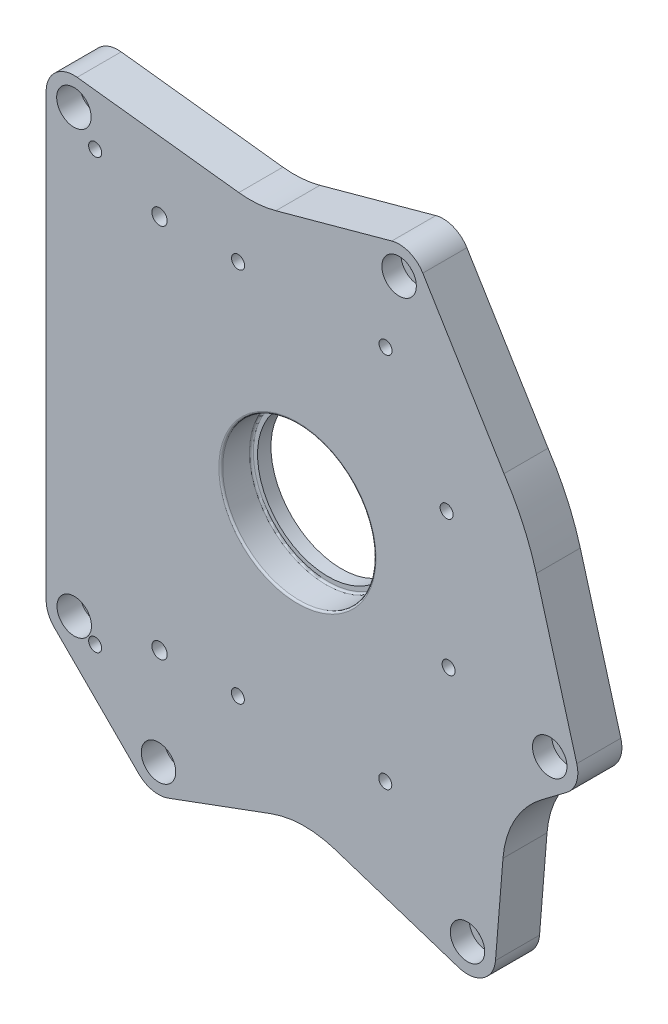
SolidWorks part; units mm, degrees
material "6061-T6 (SS)"
ref_plane "Front Plane" through (0, 0, 0) normal (0, 0, 1) x (1, 0, 0)
ref_plane "Top Plane" through (0, 0, 0) normal (0, 1, 0) x (1, 0, 0)
ref_plane "Right Plane" through (0, 0, 0) normal (1, 0, 0) x (0, 0, -1)
sketch "Sketch1" plane through (0, 0, 0) normal (0, 0, 1) x (1, 0, 0)
  line L0 (84.2211, -163.4901) -> (2.6993, -136.8316)
  line L1 (-67.4584, -162.7302) -> (2.6993, -136.8316)
  line L2 (-82.9108, -159.3414) -> (-126.9141, -115.3364)
  line L3 (140.5448, -56.1387) -> (109.1493, -79.774)
  line L4 (103.4012, -150.7323) -> (109.1493, -79.774)
  line L5 (145.8454, -40.4558) -> (124.6838, 34.9416)
  line L6 (65.4504, 141.1198) -> (107.841, 71.6428)
  line L9 (49.2431, 147.5528) -> (-20.7968, 128.3749)
  line L13 (-115.0226, 139.4368) -> (-20.7968, 128.3749)
  line L14 (-131.2133, 125.0355) -> (-131.2102, -104.9645)
  arc A2 (-115.0226, 139.4368) -> (-131.2133, 125.0355) centre (-116.7133, 125.0357) ccw
  circle A3 centre (-116.7133, 125.0357) radius 3.5 construction
  arc A6 (65.4504, 141.1198) -> (49.2431, 147.5528) centre (53.0725, 133.5676) ccw
  circle A7 centre (-76.5534, 103.7539) radius 2.5 construction
  arc A9 (-131.2102, -104.9645) -> (-126.9141, -115.3364) centre (-116.5415, -104.9643) ccw
  circle A10 centre (-116.5415, -104.9643) radius 3.5 construction
  arc A12 (-82.9108, -159.3414) -> (-67.4584, -162.7302) centre (-72.5383, -148.9692) ccw
  circle A13 centre (-72.5383, -148.9692) radius 3.5 construction
  arc A15 (84.2211, -163.4901) -> (103.4012, -150.7323) centre (88.7803, -149.548) ccw
  arc A17 (140.5448, -56.1387) -> (145.8454, -40.4558) centre (131.7224, -44.4197) ccw
  circle A18 centre (59.1026, -114.9804) radius 2.5 construction
  circle A23 centre (88.7803, -149.548) radius 3.5 construction
  circle A27 centre (131.7224, -44.4197) radius 3.5 construction
  arc A30 (124.6838, 34.9416) -> (107.841, 71.6428) centre (-0.017, -0.0702) ccw
  circle A31 centre (53.0725, 133.5676) radius 3.5 construction
  dimension "D1" = 14.5
  dimension "D2" = 7
  dimension "D3" = 5
extrude "Boss-Extrude1" add sketch "Sketch1" along normal blind 23 contours L5 A30 L6 A6 L9 L13 A2 L14 A9 L2 A12 L1 L0 A15 L4 L3 A17 A31 A3 A7 A10 A13 A18 A23 A27
fillet "Fillet2" radius 50.8 3 edges at (-20.7968, 128.3749, 11.5) (109.1493, -79.774, 11.5) (2.6993, -136.8316, 11.5)
sketch "Sketch2" plane through (0, 0, 23) normal (0, 0, -1) x (-1, 0, 0)
  circle A0 centre (0, 0) radius 40.05
  dimension "D1" = 80.1
extrude "Cut-Extrude1" cut sketch "Sketch2" along normal blind 16
sketch "Sketch5" plane through (0, 0, 23) normal (0, 0, -1) x (-1, 0, 0)
  circle A0 centre (0, 0) radius 36.83
  dimension "D1" = 73.66
extrude "Cut-Extrude2" cut sketch "Sketch5" along normal blind 25.4
sketch "Sketch6" plane through (0, 0, 0) normal (0, 0, 1) x (1, 0, 0)
  circle A0 centre (0, 0) radius 50.8 construction
  point P14 (0, 0)
  dimension "D2" = 101.6
fillet "Fillet5" radius 1 1 edges at (-40.05, 0, 23)
fillet "Fillet6" radius 1 1 edges at (-40.05, 0, 7)
sketch "Sketch43" plane through (0, 0, 23) normal (0, 0, 1) x (1, 0, 0)
  line L13 (0, 0) -> (150.4649, 0) construction
  line L14 (-31.12, -98.35) -> (-105.6166, -112.2929) construction
  line L15 (-31, 98) -> (-105.6166, 111.6261) construction
  line L16 (-105.6166, -112.2929) -> (-105.6166, 111.6261) construction
  line L17 (0, 0) -> (-105.6166, 111.6261) construction
  line L18 (-31, 98) -> (0, 0) construction
  line L19 (0, 0) -> (46, 97.92) construction
  line L20 (77.9, 39.75) -> (0, 0) construction
  line L21 (0, 0) -> (-72, -98.1221) construction
  line L22 (0, 0) -> (78.925, -30.46) construction
  line L23 (45.85, -98.52) -> (0, 0) construction
  line L24 (0, 0) -> (-72, 97.9779) construction
  line L25 (0, 0) -> (-31.12, -98.35) construction
  line L26 (-105.6166, -112.2929) -> (0, 0) construction
  circle A8 centre (0, 0) radius 46.4211 construction
  circle A12 centre (-46.643, -71.23) radius 11.3319 construction
  circle A13 centre (-72, 97.9779) radius 3.9701
  circle A14 centre (-72, -98.1221) radius 3.9701
  circle A15 centre (-105.6166, 111.6261) radius 3
  circle A16 centre (-31, 98) radius 3
  circle A17 centre (46, 97.92) radius 3
  circle A18 centre (77.9, 39.75) radius 3
  circle A19 centre (78.925, -30.46) radius 3
  circle A20 centre (45.85, -98.52) radius 3
  circle A21 centre (-31.12, -98.35) radius 3
  circle A22 centre (-105.6166, -112.2929) radius 3
  circle A23 centre (0, 0) radius 36.83 construction
  point P2 (44.5749, -98.52)
  dimension "D2" = 45.85
  dimension "D3" = 31.12
  dimension "D1" = 98.52
  dimension "D4" = 98.35
  dimension "D5" = 98.1221
  dimension "D6" = 72
  dimension "D7" = 105.6166
  dimension "D8" = 105.6166
  dimension "D9" = 72
  dimension "D10" = 31
  dimension "D11" = 46
  dimension "D12" = 77.9
  dimension "D13" = 78.925
  dimension "D14" = 39.75
  dimension "D15" = 30.46
  dimension "D16" = 97.92
  dimension "D17" = 98
  dimension "D18" = 97.9779
  dimension "D19" = 111.6261
  dimension "D20" = 112.2929
  dimension "D21" = 196.1
  dimension "D22" = 7.9403
  dimension "D23" = 6
sketch "Sketch59" plane through (0, 0, 23) normal (0, 0, 1) x (1, 0, 0)
  line L0 (145.8454, -40.4558) -> (124.6838, 34.9416) construction
  line L1 (140.5448, -56.1387) -> (127.387, -66.0442) construction
  line L2 (103.4012, -150.7323) -> (107.3061, -102.5275) construction
  line L3 (84.2211, -163.4901) -> (19.4993, -142.3254) construction
  line L4 (-67.4584, -162.7302) -> (-13.8824, -142.9527) construction
  line L5 (-82.9108, -159.3414) -> (-126.9141, -115.3364) construction
  line L6 (65.4504, 141.1198) -> (107.841, 71.6428) construction
  line L7 (49.2431, 147.5528) -> (-11.269, 130.9837) construction
  line L8 (-115.0226, 139.4368) -> (-30.608, 129.5267) construction
  line L9 (-131.2133, 125.0355) -> (-131.2102, -104.9645) construction
  line L10 (145.8454, -40.4558) -> (124.6838, 34.9416)
  line L11 (140.5448, -56.1387) -> (127.387, -66.0442)
  line L12 (103.4012, -150.7323) -> (107.3061, -102.5275)
  line L13 (84.2211, -163.4901) -> (19.4993, -142.3254)
  line L14 (-67.4584, -162.7302) -> (-13.8824, -142.9527)
  line L15 (-82.9108, -159.3414) -> (-126.9141, -115.3364)
  line L16 (65.4504, 141.1198) -> (107.841, 71.6428)
  line L17 (49.2431, 147.5528) -> (-11.269, 130.9837)
  line L18 (-115.0226, 139.4368) -> (-30.608, 129.5267)
  line L19 (-131.2133, 125.0355) -> (-131.2102, -104.9645)
  line L30 (49.2431, 147.5528) -> (-20.7968, 128.3749)
  line L31 (107.841, 71.6428) -> (65.4504, 141.1198)
  line L32 (145.8454, -40.4558) -> (124.6838, 34.9416)
  line L33 (109.1493, -79.774) -> (140.5448, -56.1387)
  line L34 (103.4012, -150.7323) -> (109.1493, -79.774)
  line L35 (2.6993, -136.8316) -> (84.2211, -163.4901)
  line L36 (-67.4584, -162.7302) -> (2.6993, -136.8316)
  line L37 (-126.9141, -115.3364) -> (-82.9108, -159.3414)
  line L38 (-131.2133, 125.0355) -> (-131.2102, -104.9645)
  line L39 (-20.7968, 128.3749) -> (-115.0226, 139.4368)
  line L40 (49.2431, 147.5528) -> (-20.7968, 128.3749)
  line L41 (107.841, 71.6428) -> (65.4504, 141.1198)
  line L42 (145.8454, -40.4558) -> (124.6838, 34.9416)
  line L43 (109.1493, -79.774) -> (140.5448, -56.1387)
  line L44 (103.4012, -150.7323) -> (109.1493, -79.774)
  line L45 (2.6993, -136.8316) -> (84.2211, -163.4901)
  line L46 (-67.4584, -162.7302) -> (2.6993, -136.8316)
  line L47 (-126.9141, -115.3364) -> (-82.9108, -159.3414)
  line L48 (-131.2133, 125.0355) -> (-131.2102, -104.9645)
  line L49 (-20.7968, 128.3749) -> (-115.0226, 139.4368)
  arc A0 (124.6838, 34.9416) -> (107.841, 71.6428) centre (-0.017, -0.0702) ccw construction
  arc A1 (140.5448, -56.1387) -> (145.8454, -40.4558) centre (131.7224, -44.4197) ccw construction
  arc A2 (127.387, -66.0442) -> (107.3061, -102.5275) centre (157.9402, -106.6292) ccw construction
  arc A3 (84.2211, -163.4901) -> (103.4012, -150.7323) centre (88.7803, -149.548) ccw construction
  arc A4 (19.4993, -142.3254) -> (-13.8824, -142.9527) centre (3.7099, -190.6093) ccw construction
  arc A5 (-82.9108, -159.3414) -> (-67.4584, -162.7302) centre (-72.5383, -148.9692) ccw construction
  arc A6 (-131.2102, -104.9645) -> (-126.9141, -115.3364) centre (-116.5415, -104.9643) ccw construction
  arc A7 (65.4504, 141.1198) -> (49.2431, 147.5528) centre (53.0725, 133.5676) ccw construction
  arc A8 (-30.608, 129.5267) -> (-11.269, 130.9837) centre (-24.6849, 179.9802) ccw construction
  arc A9 (-115.0226, 139.4368) -> (-131.2133, 125.0355) centre (-116.7133, 125.0357) ccw construction
  arc A10 (124.6838, 34.9416) -> (107.841, 71.6428) centre (-0.017, -0.0702) ccw
  arc A11 (140.5448, -56.1387) -> (145.8454, -40.4558) centre (131.7224, -44.4197) ccw
  arc A12 (127.387, -66.0442) -> (107.3061, -102.5275) centre (157.9402, -106.6292) ccw
  arc A13 (84.2211, -163.4901) -> (103.4012, -150.7323) centre (88.7803, -149.548) ccw
  arc A14 (19.4993, -142.3254) -> (-13.8824, -142.9527) centre (3.7099, -190.6093) ccw
  arc A15 (-82.9108, -159.3414) -> (-67.4584, -162.7302) centre (-72.5383, -148.9692) ccw
  arc A16 (-131.2102, -104.9645) -> (-126.9141, -115.3364) centre (-116.5415, -104.9643) ccw
  arc A17 (65.4504, 141.1198) -> (49.2431, 147.5528) centre (53.0725, 133.5676) ccw
  arc A18 (-30.608, 129.5267) -> (-11.269, 130.9837) centre (-24.6849, 179.9802) ccw
  arc A19 (-115.0226, 139.4368) -> (-131.2133, 125.0355) centre (-116.7133, 125.0357) ccw
  circle A20 centre (-116.7133, 125.0357) radius 3.5 construction
  circle A21 centre (-76.5534, 103.7539) radius 2.5 construction
  circle A22 centre (-116.5415, -104.9643) radius 3.5 construction
  circle A23 centre (-72.5383, -148.9692) radius 3.5 construction
  circle A24 centre (59.1026, -114.9804) radius 2.5 construction
  circle A25 centre (88.7803, -149.548) radius 3.5 construction
  circle A26 centre (131.7224, -44.4197) radius 3.5 construction
  arc A27 (65.4504, 141.1198) -> (49.2431, 147.5528) centre (53.0725, 133.5676) ccw
  arc A28 (124.6838, 34.9416) -> (107.841, 71.6428) centre (-0.017, -0.0702) ccw
  arc A29 (140.5448, -56.1387) -> (145.8454, -40.4558) centre (131.7224, -44.4197) ccw
  arc A30 (84.2211, -163.4901) -> (103.4012, -150.7323) centre (88.7803, -149.548) ccw
  arc A31 (-82.9108, -159.3414) -> (-67.4584, -162.7302) centre (-72.5383, -148.9692) ccw
  arc A32 (-131.2102, -104.9645) -> (-126.9141, -115.3364) centre (-116.5415, -104.9643) ccw
  arc A33 (-115.0226, 139.4368) -> (-131.2133, 125.0355) centre (-116.7133, 125.0357) ccw
  arc A34 (65.4504, 141.1198) -> (49.2431, 147.5528) centre (53.0725, 133.5676) ccw
  arc A35 (124.6838, 34.9416) -> (107.841, 71.6428) centre (-0.017, -0.0702) ccw
  arc A36 (140.5448, -56.1387) -> (145.8454, -40.4558) centre (131.7224, -44.4197) ccw
  arc A37 (84.2211, -163.4901) -> (103.4012, -150.7323) centre (88.7803, -149.548) ccw
  arc A38 (-82.9108, -159.3414) -> (-67.4584, -162.7302) centre (-72.5383, -148.9692) ccw
  arc A39 (-131.2102, -104.9645) -> (-126.9141, -115.3364) centre (-116.5415, -104.9643) ccw
  arc A40 (-115.0226, 139.4368) -> (-131.2133, 125.0355) centre (-116.7133, 125.0357) ccw
  circle A41 centre (53.0725, 133.5676) radius 3.5 construction
  dimension "D1" = 0
hole_wizard "CBORE for M10 SHCS7" positions "Sketch62" profile "Sketch63" counterbore size "M10" standard "ANSI Metric" end condition through all
sketch "Sketch62" plane through (0, 0, 23) normal (0, 0, 1) x (1, 0, 0)
  point P0 (-116.7133, 125.0357)
  point P3 (-116.5415, -104.9643)
  point P7 (-72.5383, -148.9692)
sketch "Sketch63" plane through (-116.7133, 125.0357, 23) normal (1, 0, 0) x (0, -1, 0)
  line L0 (0, 0) -> (0, 23)
  line L1 (0, 23) -> (5.25, 23)
  line L3 (5.25, 23) -> (5.25, 12)
  line L4 (5.25, 12) -> (9, 12)
  line L5 (9, 12) -> (9, 0)
  line L7 (9, 0) -> (0, 0)
  line L11 (0, -6.35) -> (0, 107.95) construction
  dimension "Thru Hole Dia." = 10.5
  dimension "Thru Hole Depth" = 23
  dimension "C'Bore Dia." = 18
  dimension "C'Bore Depth" = 12
hole_wizard "Tap Drill for M8x1.25 Tap2" positions "Sketch66" profile "Sketch67" hole size "M8x1.25" standard "ANSI Metric" end condition through all
sketch "Sketch66" plane through (0, 0, 23) normal (0, 0, 1) x (1, 0, 0)
  point P0 (46, 97.92)
  point P3 (-31, 98)
  point P6 (-105.6166, 111.6261)
  point P9 (-105.6166, -112.2929)
  point P12 (-31.12, -98.35)
  point P15 (45.85, -98.52)
  point P18 (78.925, -30.46)
  point P21 (77.9, 39.75)
sketch "Sketch67" plane through (46, 97.92, 23) normal (1, 0, 0) x (0, -1, 0)
  line L0 (0, 0) -> (0, 23)
  line L1 (0, 23) -> (3.4, 23)
  line L2 (3.4, 23) -> (3.4, 0)
  line L5 (3.4, 0) -> (0, 0)
  line L11 (0, -6.35) -> (0, 107.95) construction
  dimension "Thru Hole Dia." = 6.8
  dimension "Thru Hole Depth" = 23
hole_wizard "Ø8.0mm Dowel Hole1" positions "Sketch70" profile "Sketch71" hole size "Ø8.0" standard "ANSI Metric"
sketch "Sketch70" plane through (0, 0, 23) normal (0, 0, 1) x (1, 0, 0)
  point P0 (-72, 97.9779)
  point P3 (-72, -98.1221)
sketch "Sketch71" plane through (-72, 97.9779, 23) normal (1, 0, 0) x (0, -1, 0)
  line L0 (0, 0) -> (0, 11.4034)
  line L1 (0, 11.4034) -> (4, 9)
  line L2 (4, 9) -> (4, 0)
  line L5 (4, 0) -> (0, 0)
  line L10 (0, 11.4034) -> (-4, 9) construction
  line L11 (0, -6.35) -> (0, 107.95) construction
  dimension "Hole Dia." = 8
  dimension "Hole Depth" = 9
  dimension "Drill Angle" = 118
hole_wizard "Ø10.0mm Dowel Hole3" positions "Sketch72" profile "Sketch73" hole size "Ø10.0" standard "ANSI Metric"
sketch "Sketch72" plane through (0, 0, 0) normal (0, 0, -1) x (-1, 0, 0)
  point P0 (76.5534, 103.7539)
  point P3 (-59.1026, -114.9804)
sketch "Sketch73" plane through (-76.5534, 103.7539, 0) normal (1, 0, 0) x (0, 1, 0)
  line L0 (0, 0) -> (0, 13.0043)
  line L1 (0, 13.0043) -> (5, 10)
  line L2 (5, 10) -> (5, 0)
  line L5 (5, 0) -> (0, 0)
  line L10 (0, 13.0043) -> (-5, 10) construction
  line L11 (0, -6.35) -> (0, 107.95) construction
  dimension "Hole Dia." = 10
  dimension "Hole Depth" = 10
  dimension "Drill Angle" = 118
hole_wizard "CBORE for M10 SHCS9" positions "Sketch74" profile "Sketch75" counterbore size "M10" standard "ANSI Metric" end condition through all
sketch "Sketch74" plane through (0, 0, 23) normal (0, 0, 1) x (1, 0, 0)
  point P0 (53.0725, 133.5676)
  point P3 (131.7224, -44.4197)
  point P6 (88.7803, -149.548)
sketch "Sketch75" plane through (53.0725, 133.5676, 23) normal (1, 0, 0) x (0, -1, 0)
  line L0 (0, 0) -> (0, 23)
  line L1 (0, 23) -> (5.25, 23)
  line L3 (5.25, 23) -> (5.25, 10)
  line L4 (5.25, 10) -> (9, 10)
  line L5 (9, 10) -> (9, 0)
  line L7 (9, 0) -> (0, 0)
  line L11 (0, -6.35) -> (0, 107.95) construction
  dimension "Thru Hole Dia." = 10.5
  dimension "Thru Hole Depth" = 23
  dimension "C'Bore Dia." = 18
  dimension "C'Bore Depth" = 10
